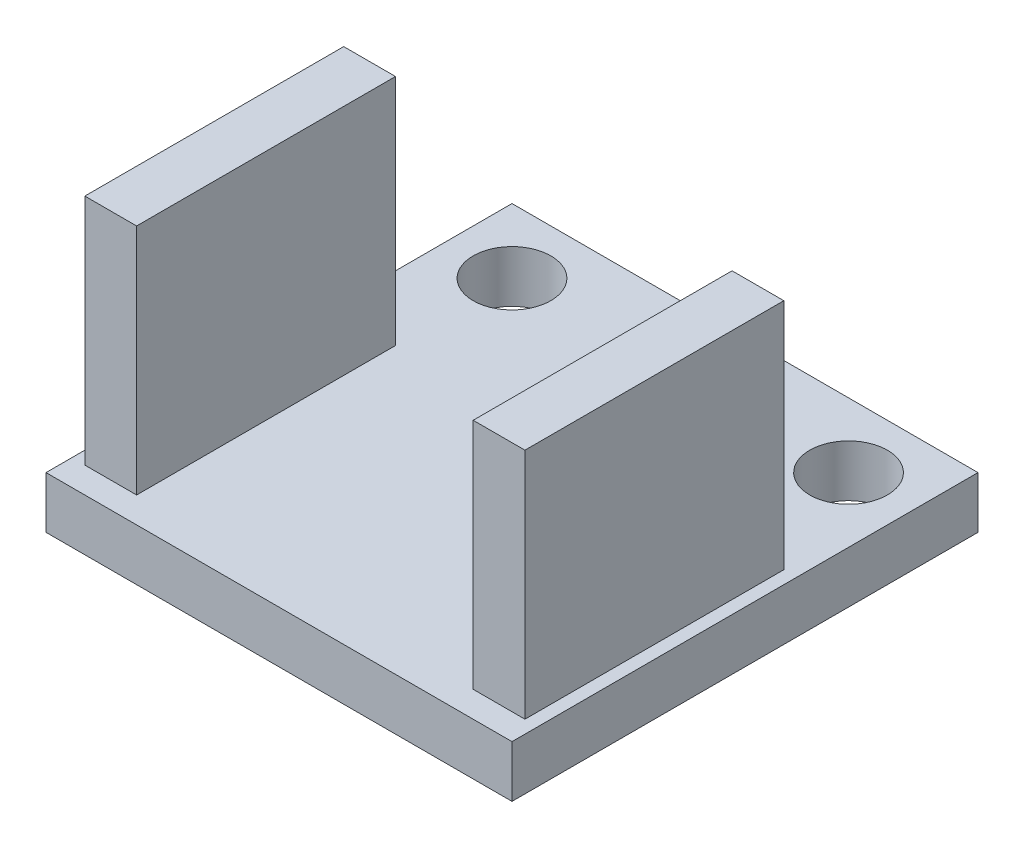
SolidWorks part; units mm, degrees
ref_plane "Front Plane" through (0, 0, 0) normal (0, 0, 1) x (1, 0, 0)
ref_plane "Top Plane" through (0, 0, 0) normal (0, 1, 0) x (1, 0, 0)
ref_plane "Right Plane" through (0, 0, 0) normal (1, 0, 0) x (0, 0, -1)
sketch "Sketch1" plane through (0, 0, 0) normal (0, 1, 0) x (1, 0, 0)
  line L1 (0, 0) -> (18, 0)
  line L2 (0, 0) -> (0, -18)
  line L3 (0, -18) -> (18, -18)
  line L4 (18, 0) -> (18, -18)
  dimension "D1" = 18
extrude "Boss-Extrude1" add sketch "Sketch1" along normal blind 2
sketch "Sketch2" plane through (0, 2, 0) normal (0, 1, 0) x (1, 0, 0)
  line L0 (18, 0) -> (0, 0) construction
  line L1 (0, 0) -> (0, -18) construction
  line L2 (18, -18) -> (18, 0) construction
  circle A0 centre (2.5, -2.5) radius 1.5
  circle A1 centre (15.5, -2.5) radius 1.5
  point P12 (15.6765, -1.4388)
  point P13 (15.9548, 0)
  dimension "D1" = 3
  dimension "D2" = 2.5
  dimension "D3" = 2.5
  dimension "D4" = 2.5
  dimension "D5" = 2.5
extrude "Cut-Extrude1" cut sketch "Sketch2" against normal blind 2
sketch "Sketch3" plane through (0, 2, 0) normal (0, 1, 0) x (1, 0, 0)
  line L0 (0, -18) -> (18, -18) construction
  line L5 (0.5, -7) -> (2.5, -7)
  line L6 (0.5, -7) -> (0.5, -17)
  line L7 (0.5, -17) -> (2.5, -17)
  line L8 (2.5, -7) -> (2.5, -17)
  line L9 (15.5, -7) -> (17.5, -7)
  line L10 (15.5, -7) -> (15.5, -17)
  line L11 (15.5, -17) -> (17.5, -17)
  line L12 (17.5, -7) -> (17.5, -17)
  line L13 (0, 0) -> (0, -18) construction
  line L14 (18, -18) -> (18, 0) construction
  point P12 (16.5, -17)
  dimension "D1" = 10
  dimension "D2" = 1
  dimension "D3" = 0.5
  dimension "D4" = 2
  dimension "D5" = 1
  dimension "D6" = 0.5
  dimension "D7" = 2
  dimension "D8" = 10
extrude "Boss-Extrude2" add sketch "Sketch3" along normal blind 9
